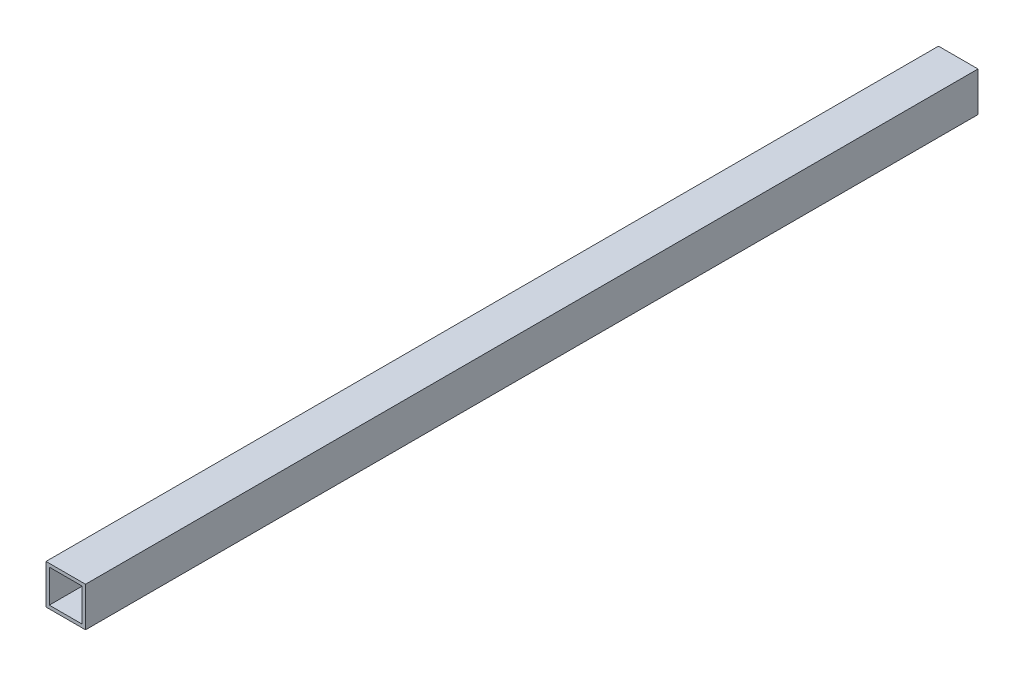
SolidWorks part; units mm, degrees
ref_plane "前视基准面" through (0, 0, 0) normal (0, 0, 1) x (1, 0, 0)
ref_plane "上视基准面" through (0, 0, 0) normal (0, 1, 0) x (1, 0, 0)
ref_plane "右视基准面" through (0, 0, 0) normal (1, 0, 0) x (0, 0, -1)
sketch "草图1" plane through (0, 0, 0) normal (0, 0, 1) x (1, 0, 0)
  line L0 (-12, 12) -> (12, 12)
  line L1 (-10, 10) -> (10, 10)
  line L2 (-10, 10) -> (-10, -10)
  line L3 (-10, -10) -> (10, -10)
  line L4 (10, 10) -> (10, -10)
  line L5 (-10, 10) -> (10, -10) construction
  line L6 (-10, -10) -> (10, 10) construction
  line L7 (12, 12) -> (12, -12)
  line L8 (-12, -12) -> (12, -12)
  line L9 (-12, 12) -> (-12, -12)
  point P0 (0, 0)
  dimension "D1" = 20
  dimension "D2" = 20
  dimension "D3" = 2
extrude "凸台-拉伸1" add sketch "草图1" along normal blind 542
